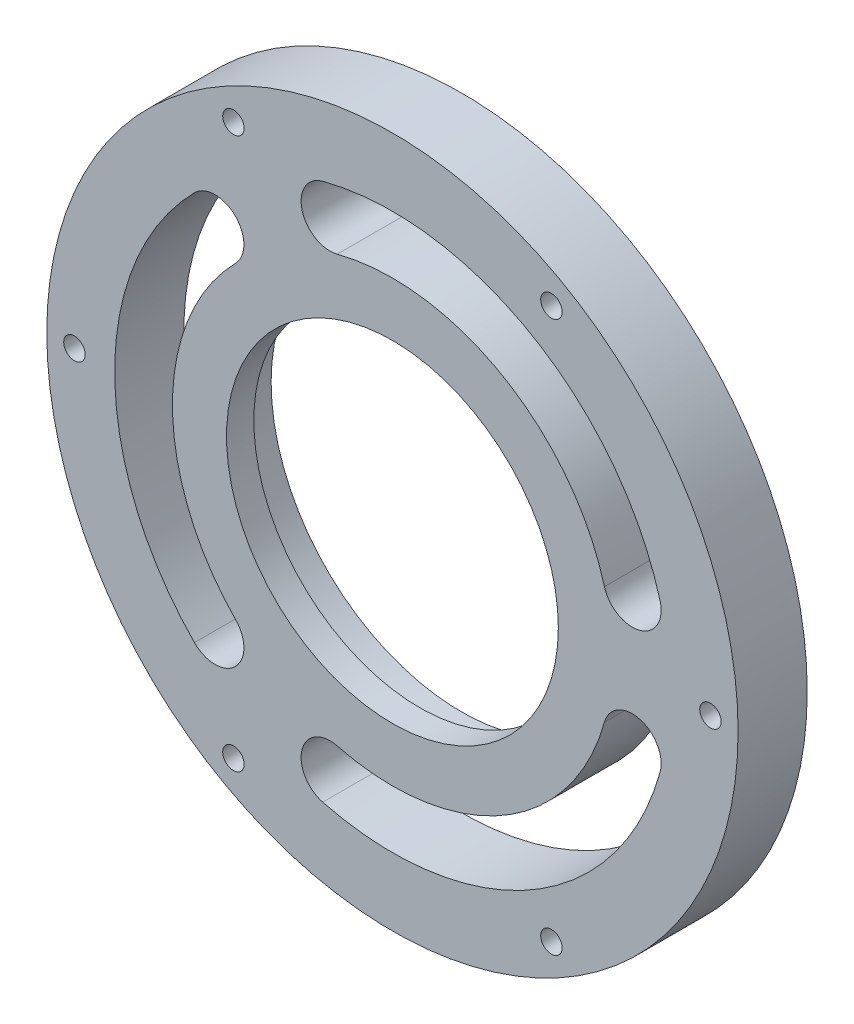
SolidWorks part; units mm, degrees
ref_plane "前视基准面" through (0, 0, 0) normal (0, 0, 1) x (1, 0, 0)
ref_plane "上视基准面" through (0, 0, 0) normal (0, 1, 0) x (1, 0, 0)
ref_plane "右视基准面" through (0, 0, 0) normal (1, 0, 0) x (0, 0, -1)
other "Configuration Table"
sketch "草图1" plane through (0, 0, 0) normal (0, 0, 1) x (1, 0, 0)
  line L0 (42, 0) -> (50, 0) construction
  circle A0 centre (0, 0) radius 50
  circle A1 centre (0, 0) radius 42
  circle A2 centre (46, 0) radius 1.55
  circle A3 centre (23, -39.8372) radius 1.55
  circle A4 centre (-23, -39.8372) radius 1.55
  circle A5 centre (-46, 0) radius 1.55
  circle A6 centre (-23, 39.8372) radius 1.55
  circle A7 centre (23, 39.8372) radius 1.55
  point P20 (0, 0)
  dimension "D1" = 100
  dimension "D2" = 8
  dimension "D3" = 3.1
  dimension "D4" = 6
extrude "凸台-拉伸1" add sketch "草图1" along normal blind 10
sketch "草图3" plane through (0, 0, 10) normal (0, 0, 1) x (1, 0, 0)
  circle A0 centre (0, 0) radius 42
  circle A1 centre (0, 0) radius 27.55
  dimension "D1" = 84
  dimension "D2" = 55.1
extrude "凸台-拉伸2" add sketch "草图3" against normal blind 10
sketch "草图5" plane through (0, 0, 10) normal (0, 0, 1) x (1, 0, 0)
  circle A0 centre (0, 0) radius 28.649
  circle A1 centre (0, 0) radius 24
  dimension "D2" = 48
extrude "凸台-拉伸4" add sketch "草图5" against normal blind 3.95
sketch "草图6" plane through (0, 0, 0) normal (0, 0, -1) x (-1, 0, 0)
  line L0 (-23, 39.8372) -> (0, 0) construction
  arc A0 (-34.6965, 9.5995) -> (9.0349, 34.8478) centre (0, 0) cw construction
  arc A1 (10.0834, 38.8919) -> (-38.723, 10.7135) centre (0, 0) ccw
  arc A2 (7.9864, 30.8038) -> (-30.6701, 8.4855) centre (0, 0) ccw
  arc A3 (7.9864, 30.8038) -> (10.0834, 38.8919) centre (9.0349, 34.8478) ccw
  arc A4 (-38.723, 10.7135) -> (-30.6701, 8.4855) centre (-34.6965, 9.5995) ccw
  arc A5 (25.6617, 25.2484) -> (25.6617, -25.2484) centre (0, 0) cw construction
  arc A6 (28.6397, -28.1784) -> (28.6397, 28.1784) centre (0, 0) ccw
  arc A7 (22.6837, -22.3183) -> (22.6837, 22.3183) centre (0, 0) ccw
  arc A8 (22.6837, -22.3183) -> (28.6397, -28.1784) centre (25.6617, -25.2484) ccw
  arc A9 (28.6397, 28.1784) -> (22.6837, 22.3183) centre (25.6617, 25.2484) ccw
  arc A10 (9.0349, -34.8478) -> (-34.6965, -9.5995) centre (0, 0) cw construction
  arc A11 (-38.723, -10.7135) -> (10.0834, -38.8919) centre (0, 0) ccw
  arc A12 (-30.6701, -8.4855) -> (7.9864, -30.8038) centre (0, 0) ccw
  arc A13 (-30.6701, -8.4855) -> (-38.723, -10.7135) centre (-34.6965, -9.5995) ccw
  arc A14 (10.0834, -38.8919) -> (7.9864, -30.8038) centre (9.0349, -34.8478) ccw
  point P0 (0, 0)
  point P1 (-18, 31.1769)
  point P10 (36, 0)
  point P21 (-18, -31.1769)
  point P28 (0, 0)
  dimension "D2" = 36
  dimension "D1" = 3
extrude "切除-拉伸1" cut sketch "草图6" against normal blind 10
